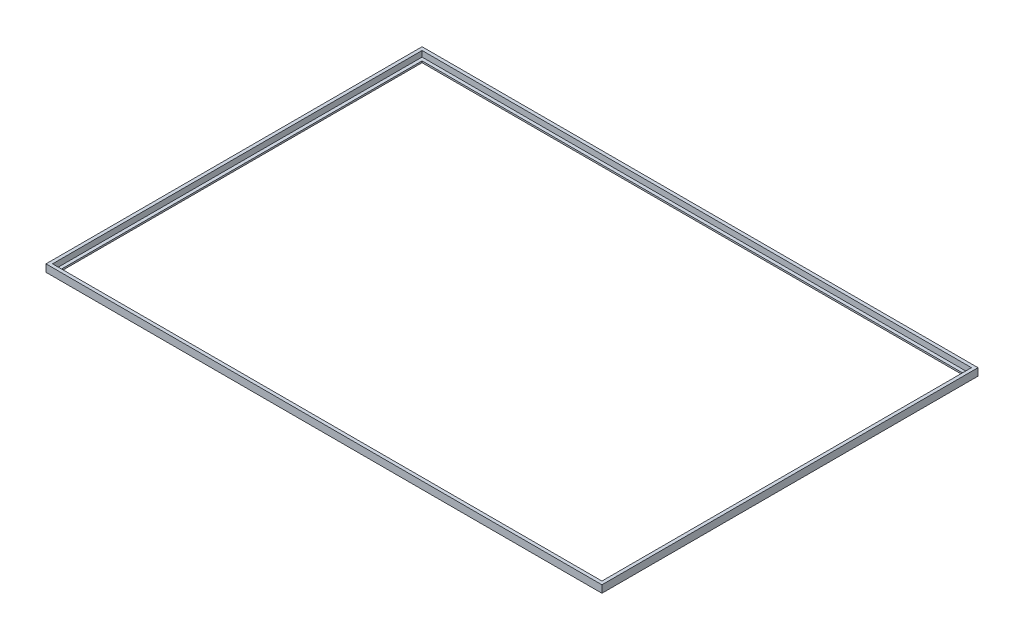
SolidWorks part; units mm, degrees
ref_plane "Front Plane" through (0, 0, 0) normal (0, 0, 1) x (1, 0, 0)
ref_plane "Top Plane" through (0, 0, 0) normal (0, 1, 0) x (1, 0, 0)
ref_plane "Right Plane" through (0, 0, 0) normal (1, 0, 0) x (0, 0, -1)
sketch "Sketch1" plane through (0, 0, 0) normal (0, 1, 0) x (1, 0, 0)
  line L0 (2, 2) -> (168, 2)
  line L1 (0, 0) -> (170, 0)
  line L2 (0, 0) -> (0, 115)
  line L3 (0, 115) -> (170, 115)
  line L4 (170, 0) -> (170, 115)
  line L5 (168, 2) -> (168, 113)
  line L6 (2, 113) -> (168, 113)
  line L7 (2, 2) -> (2, 113)
  dimension "D1" = 115
  dimension "D2" = 170
  dimension "D3" = 2
extrude "Boss-Extrude1" add sketch "Sketch1" along normal blind 2.75
sketch "Sketch2" plane through (0, 2.75, 0) normal (0, 1, 0) x (1, 0, 0)
  line L8 (169, 1) -> (169, 114)
  line L9 (169, 114) -> (1, 114)
  line L10 (1, 1) -> (169, 1)
  line L11 (1, 114) -> (1, 1)
  line L12 (169, 1) -> (169, 114)
  line L13 (169, 114) -> (1, 114)
  line L14 (1, 1) -> (169, 1)
  line L15 (1, 114) -> (1, 1)
  dimension "D1" = 1
extrude "Cut-Extrude1" cut sketch "Sketch2" against normal blind 1.75
chamfer "Chamfer1" distance 0.5 angle 45 8 edges at (168, 0, -57.5) (85, 0, -2) (2, 0, -57.5) (85, 0, -113) (85, 0, 0) (170, 0, -57.5) (85, 0, -115) (0, 0, -57.5)
